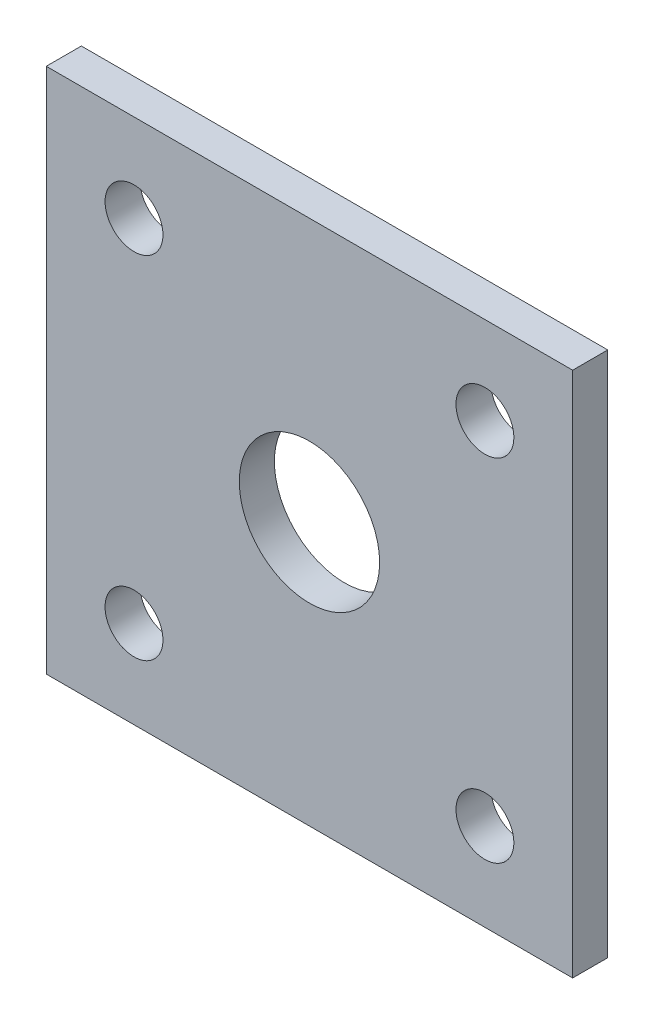
SolidWorks part; units mm, degrees
ref_plane "Plan de face" through (0, 0, 0) normal (0, 0, 1) x (1, 0, 0)
ref_plane "Plan de dessus" through (0, 0, 0) normal (0, 1, 0) x (1, 0, 0)
ref_plane "Plan de droite" through (0, 0, 0) normal (1, 0, 0) x (0, 0, -1)
sketch "Esquisse1" plane through (0, 0, 0) normal (0, 0, 1) x (1, 0, 0)
  line L0 (-46.2913, 29.5426) -> (-16.2913, 29.5426)
  line L1 (-46.2913, 29.5426) -> (-46.2913, -0.4574)
  line L2 (-16.2913, 29.5426) -> (-16.2913, -0.4574)
  line L3 (-46.2913, -0.4574) -> (-16.2913, -0.4574)
  line L4 (-31.2913, 33.1596) -> (-31.2913, -12.0177) construction
  line L5 (-49.6956, 14.5426) -> (-8.1353, 14.5426) construction
  circle A0 centre (-41.2913, 24.5426) radius 1.65
  circle A1 centre (-21.2913, 24.5426) radius 1.65
  circle A2 centre (-21.2913, 4.5426) radius 1.65
  circle A3 centre (-41.2913, 4.5426) radius 1.65
  circle A4 centre (-31.2913, 14.5426) radius 4
  point P8 (-16.2913, 14.5426)
  point P9 (-31.2913, 29.5426)
  point P12 (-31.2913, 14.5426)
  point P22 (-31.2913, 14.5426)
  dimension "D3" = 3.3
  dimension "D1" = 30
  dimension "D2" = 30
  dimension "D4" = 5
  dimension "D5" = 5
  dimension "D6" = 4
extrude "Boss.-Extru.1" add sketch "Esquisse1" along normal blind 2
